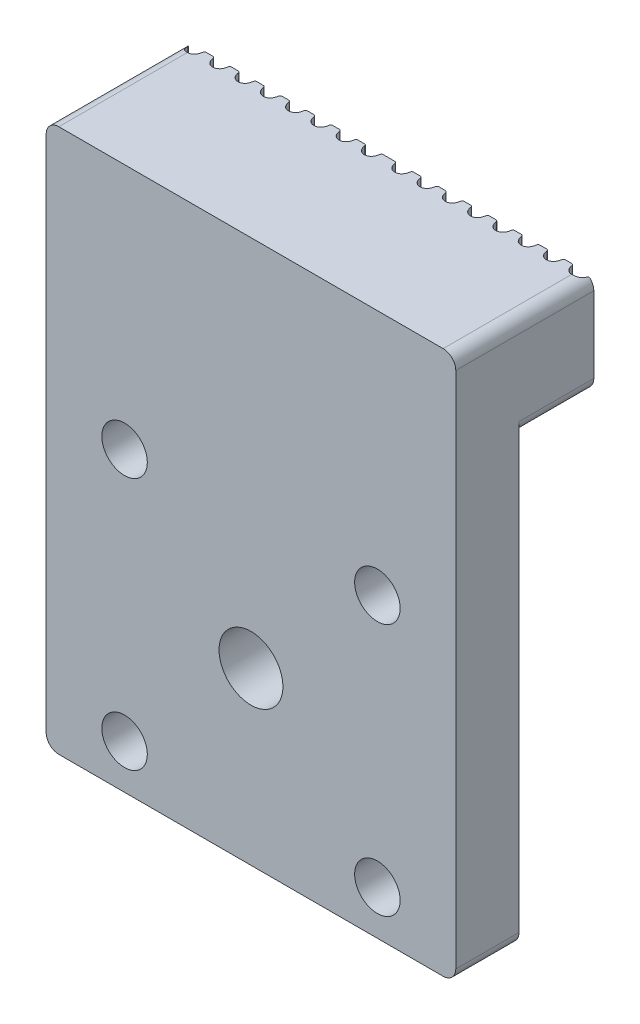
SolidWorks part; units mm, degrees
material "ABS"
ref_plane "Front Plane" through (0, 0, 0) normal (0, 0, 1) x (1, 0, 0)
ref_plane "Top Plane" through (0, 0, 0) normal (0, 1, 0) x (1, 0, 0)
ref_plane "Right Plane" through (0, 0, 0) normal (1, 0, 0) x (0, 0, -1)
sketch "Sketch1" plane through (0, 0, 0) normal (0, 0, 1) x (1, 0, 0)
  line L1 (-16.2, -13.5) -> (16.2, -13.5)
  line L2 (-16.2, -13.5) -> (-16.2, 13.5)
  line L3 (-16.2, 13.5) -> (16.2, 13.5)
  line L4 (16.2, -13.5) -> (16.2, 13.5)
  line L5 (-16.2, -13.5) -> (16.2, 13.5) construction
  line L6 (-16.2, 13.5) -> (16.2, -13.5) construction
  point P0 (0, 0)
  dimension "D1" = 32.4
  dimension "D2" = 27
extrude "Boss-Extrude1" add sketch "Sketch1" along normal blind 5
hole_wizard "M3 Clearance Hole1" positions "Sketch3" profile "Sketch4" hole size "M3" standard "ANSI Metric" end condition through all
sketch "Sketch3" plane through (0, 0, 5) normal (0, 0, 1) x (1, 0, 0)
  point P0 (10, -10)
  point P2 (-10, -10)
  point P4 (-10, 10)
  point P6 (10, 10)
sketch "Sketch4" plane through (10, -10, 5) normal (1, 0, 0) x (0, -1, 0)
  line L0 (0, 0) -> (0, 5)
  line L1 (0, 5) -> (1.8, 5)
  line L2 (1.8, 5) -> (1.8, 0)
  line L5 (1.8, 0) -> (0, 0)
  line L11 (0, -6.35) -> (0, 107.95) construction
  dimension "Thru Hole Dia." = 3.6
  dimension "Thru Hole Depth" = 5
ref_plane "Plane1" through (0, 0, 0) normal (-1, 0, 0) x (0, 0, 1)
sketch "Sketch10" plane through (0, 0, 0) normal (0, 0, -1) x (-1, 0, 0)
  circle A0 centre (0, 0) radius 2.5273
  dimension "D1" = 5.0546
extrude "Cut-Extrude5" cut sketch "Sketch10" against normal through all
sketch "Sketch11" plane through (16.2, 0, 0) normal (1, 0, 0) x (0, 0, -1)
  line L0 (-5, 13.5) -> (-5, 29.5)
  line L1 (-5, 29.5) -> (6.55, 29.5)
  line L2 (6.55, 29.5) -> (6.55, 21.5)
  line L3 (6.55, 21.5) -> (0, 21.5)
  line L4 (0, 21.5) -> (0, 13.5)
  line L5 (0, 13.5) -> (-5, 13.5)
  dimension "D1" = 16
  dimension "D2" = 8
  dimension "D3" = 6.55
extrude "Boss-Extrude2" add sketch "Sketch11" against normal up to surface (32.4 mm away) up to face at (-16.2, 0, 2.5)
sketch "Sketch13" plane through (0, 29.5, 0) normal (0, 1, 0) x (1, 0, 0)
  line L0 (-16.2, 6.55) -> (-12.2, 6.55)
  line L1 (-14.4598, 5.92) -> (-13.9402, 5.92)
  line L2 (-13.2, 5.17) -> (-13.2, 4.5354) construction
  line L3 (-12.2, 5.92) -> (-12.4598, 5.92)
  line L4 (-16.3239, 6.174) -> (-11.9897, 6.174) construction
  line L5 (-12.8, 3.5736) -> (-12.8, 3.9221) construction
  line L6 (-14.2, 4.5354) -> (-14.2, 2.8635) construction
  line L7 (-16.2, 5.92) -> (-15.9402, 5.92)
  line L8 (-16.3239, 5.17) -> (-11.9897, 5.17) construction
  line L9 (-16.2, 5.92) -> (-16.2, 6.55)
  line L10 (-12.2, 6.55) -> (-12.2, 5.92)
  line L11 (-16.2, -5) -> (-16.2, 6.55) construction
  line L12 (-16.2, 6.55) -> (16.2, 6.55) construction
  arc A0 (-13.6989, 5.4818) -> (-12.7011, 5.4818) centre (-13.2, 5.725) ccw
  arc A1 (-13.7915, 5.7896) -> (-13.6989, 5.4818) centre (-12.8, 5.92) ccw
  arc A2 (-13.7915, 5.7896) -> (-13.9402, 5.92) centre (-13.9402, 5.77) ccw
  arc A3 (-12.6085, 5.7896) -> (-12.4598, 5.92) centre (-12.4598, 5.77) cw
  arc A4 (-12.6085, 5.7896) -> (-12.7011, 5.4818) centre (-13.6, 5.92) cw
  arc A5 (-14.6085, 5.7896) -> (-14.4598, 5.92) centre (-14.4598, 5.77) cw
  arc A6 (-14.6085, 5.7896) -> (-14.7011, 5.4818) centre (-15.6, 5.92) cw
  arc A7 (-15.7915, 5.7896) -> (-15.9402, 5.92) centre (-15.9402, 5.77) ccw
  arc A8 (-15.7915, 5.7896) -> (-15.6989, 5.4818) centre (-14.8, 5.92) ccw
  arc A9 (-14.7011, 5.4818) -> (-15.6989, 5.4818) centre (-15.2, 5.725) cw
  point P25 (-14.2, 5.92)
  dimension "D1" = 1.38
  dimension "D5" = 1
  dimension "D6" = 1
  dimension "D7" = 0.15
  dimension "D8" = 0.75
  dimension "D2" = 0.555
  dimension "D3" = 0
  dimension "PLD" = 0.254
  dimension "D4" = 0.4
  dimension "D9" = 0
extrude "Cut-Extrude6" cut sketch "Sketch13" against normal up to surface (8 mm away) up to face at (0, 21.5, -3.275)
pattern_linear "LPattern1" count 4 spacing 4 along (1, 0, 0) of "Cut-Extrude6"
mirror "Mirror1" about plane through (0, 0, 0) normal (1, 0, 0) of "LPattern1", "Cut-Extrude6"
sketch "Sketch14" plane through (0, 29.5, 0) normal (0, 1, 0) x (1, 0, 0)
  line L1 (-0.2, 6.55) -> (0.2, 6.55)
  line L2 (-0.2, 6.55) -> (-0.2, 5.92)
  line L3 (-0.2, 5.92) -> (0.2, 5.92)
  line L4 (0.2, 6.55) -> (0.2, 5.92)
extrude "Cut-Extrude7" cut sketch "Sketch14" against normal up to surface (8 mm away) up to face at (0, 21.5, -5.6028)
fillet "Fillet1" radius 1 6 edges at (16.2, 21.5, -2.96) (16.2, 29.5, -0.46) (-16.2, 29.5, -0.46) (-16.2, 21.5, -2.96) (-16.2, -13.5, 2.5) (16.2, -13.5, 2.5)
